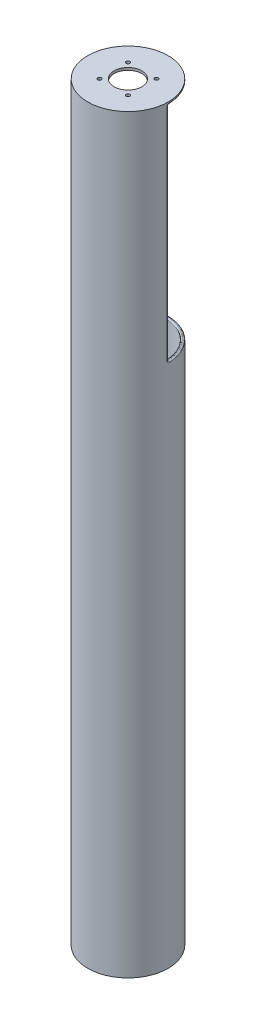
SolidWorks part; units mm, degrees
ref_plane "前视基准面" through (0, 0, 0) normal (0, 0, 1) x (1, 0, 0)
ref_plane "上视基准面" through (0, 0, 0) normal (0, 1, 0) x (1, 0, 0)
ref_plane "右视基准面" through (0, 0, 0) normal (1, 0, 0) x (0, 0, -1)
other "Configuration Table"
sketch "草图1" plane through (0, 0, 0) normal (0, 1, 0) x (1, 0, 0)
  circle A0 centre (0, 0) radius 32.5
  circle A1 centre (0, 0) radius 30
  dimension "D1" = 65
  dimension "D2" = 60
extrude "凸台-拉伸1" add sketch "草图1" along normal blind 340
sketch "草图2" plane through (0, 340, 0) normal (0, 1, 0) x (1, 0, 0)
  circle A0 centre (0, 0) radius 32.5
extrude "凸台-拉伸2" add sketch "草图2" along normal blind 5
sketch "草图8" plane through (0, 345, 0) normal (0, 1, 0) x (1, 0, 0)
  line L0 (-10.1, 10.1) -> (-10.1, -10.1) construction
  line L1 (10.1, -10.1) -> (10.1, 10.1) construction
  line L2 (-10.1, 10.1) -> (-10.1, -10.1) construction
  line L3 (10.1, -10.1) -> (10.1, 10.1) construction
  line L4 (10.3, -10.1) -> (10.3, 10.1)
  line L5 (8.1, 12.3) -> (-8.1, 12.3)
  line L6 (-10.3, 10.1) -> (-10.3, -10.1)
  line L7 (-8.1, -12.3) -> (8.1, -12.3)
  line L8 (-13.1, -3.3) -> (-13.1, 3.3) construction
  line L9 (-16.1, 2.4158) -> (-16.1, -2.4158) construction
  line L10 (-16.1, 0) -> (16.1, 0) construction
  line L11 (16.1, -2.4158) -> (16.1, 2.4158) construction
  line L12 (13.1, -3.3) -> (13.1, 3.3) construction
  line L20 (-8.7423, 11.1025) -> (-8.3294, 10.8824)
  line L21 (-9.2706, 9.1176) -> (-9.3647, 9.1678)
  line L22 (-10.1, 8.7267) -> (-10.1, 7.4004)
  line L23 (-11.416, 5.521) -> (-14.784, 4.2951)
  line L24 (-16.1, 2.4158) -> (-16.1, -2.4158)
  line L25 (-14.784, -4.2951) -> (-11.416, -5.521)
  line L26 (-10.1, -7.4004) -> (-10.1, -8.7267)
  line L27 (-9.3647, -9.1678) -> (-9.2706, -9.1176)
  line L28 (-8.3294, -10.8824) -> (-8.7423, -11.1025)
  line L29 (-8.1, -12.1) -> (8.1, -12.1)
  line L30 (8.7423, -11.1025) -> (8.3294, -10.8824)
  line L31 (9.2706, -9.1176) -> (9.3647, -9.1678)
  line L32 (10.1, -8.7267) -> (10.1, -7.4004)
  line L33 (11.416, -5.521) -> (14.784, -4.2951)
  line L34 (16.1, -2.4158) -> (16.1, 2.4158)
  line L35 (14.784, 4.2951) -> (11.416, 5.521)
  line L36 (10.1, 7.4004) -> (10.1, 8.7267)
  line L37 (9.3647, 9.1678) -> (9.2706, 9.1176)
  line L38 (8.3294, 10.8824) -> (8.7423, 11.1025)
  line L39 (8.1, 12.1) -> (-8.1, 12.1)
  line L42 (-10.1, 8.7267) -> (-10.1, 7.4004) construction
  line L46 (-10.1, -7.4004) -> (-10.1, -8.7267) construction
  line L49 (-8.1, -12.1) -> (8.1, -12.1) construction
  line L52 (10.1, -8.7267) -> (10.1, -7.4004) construction
  line L56 (10.1, 7.4004) -> (10.1, 8.7267) construction
  line L59 (8.1, 12.1) -> (-8.1, 12.1) construction
  arc A0 (-8.6427, 12.025) -> (-10.1, 10.1) centre (-8.1, 10.1) ccw construction
  arc A1 (10.1, 10.1) -> (8.6427, 12.025) centre (8.1, 10.1) ccw construction
  arc A2 (-10.1, -10.1) -> (-8.6427, -12.025) centre (-8.1, -10.1) ccw construction
  arc A3 (8.6427, -12.025) -> (10.1, -10.1) centre (8.1, -10.1) ccw construction
  arc A4 (-8.6427, 12.025) -> (-10.1, 10.1) centre (-8.1, 10.1) ccw construction
  arc A5 (10.1, 10.1) -> (8.6427, 12.025) centre (8.1, 10.1) ccw construction
  arc A6 (-10.1, -10.1) -> (-8.6427, -12.025) centre (-8.1, -10.1) ccw construction
  arc A7 (8.6427, -12.025) -> (10.1, -10.1) centre (8.1, -10.1) ccw construction
  arc A8 (10.3, 10.1) -> (8.6969, 12.2175) centre (8.1, 10.1) ccw
  arc A9 (8.6969, 12.2175) -> (8.1, 12.3) centre (8.1, 10.1) ccw
  arc A10 (-8.1, 12.3) -> (-8.6969, 12.2175) centre (-8.1, 10.1) ccw
  arc A11 (-8.6969, 12.2175) -> (-10.3, 10.1) centre (-8.1, 10.1) ccw
  arc A12 (-10.3, -10.1) -> (-8.6969, -12.2175) centre (-8.1, -10.1) ccw
  arc A13 (-8.6969, -12.2175) -> (-8.1, -12.3) centre (-8.1, -10.1) ccw
  arc A14 (8.1, -12.3) -> (8.6969, -12.2175) centre (8.1, -10.1) ccw
  arc A15 (8.6969, -12.2175) -> (10.3, -10.1) centre (8.1, -10.1) ccw
  arc A16 (-11.6, 1.8) -> (-14.6, 1.8) centre (-13.1, 1.8) ccw construction
  arc A17 (14.6, 1.8) -> (11.6, 1.8) centre (13.1, 1.8) ccw construction
  circle A18 centre (-13.1, 0) radius 1.5
  circle A19 centre (13.1, 0) radius 1.5
  arc A28 (-8.1, 12.1) -> (-8.6427, 12.025) centre (-8.1, 10.1) ccw
  arc A29 (-8.6427, 12.025) -> (-8.7423, 11.1025) centre (-8.507, 11.5437) ccw
  arc A30 (-9.2706, 9.1176) -> (-8.3294, 10.8824) centre (-8.8, 10) ccw
  arc A31 (-9.3647, 9.1678) -> (-9.6, 9.2267) centre (-9.6, 8.7267) ccw
  arc A32 (-9.6, 9.2267) -> (-10.1, 8.7267) centre (-9.6, 8.7267) ccw
  arc A33 (-11.416, 5.521) -> (-10.1, 7.4004) centre (-12.1, 7.4004) ccw
  arc A34 (-14.784, 4.2951) -> (-16.1, 2.4158) centre (-14.1, 2.4158) ccw
  arc A35 (-16.1, -2.4158) -> (-14.784, -4.2951) centre (-14.1, -2.4158) ccw
  arc A36 (-10.1, -7.4004) -> (-11.416, -5.521) centre (-12.1, -7.4004) ccw
  arc A37 (-10.1, -8.7267) -> (-9.3647, -9.1678) centre (-9.6, -8.7267) ccw
  arc A38 (-8.8, -9) -> (-9.2706, -9.1176) centre (-8.8, -10) ccw
  arc A39 (-8.3294, -10.8824) -> (-8.8, -9) centre (-8.8, -10) ccw
  arc A40 (-8.7423, -11.1025) -> (-8.6427, -12.025) centre (-8.507, -11.5437) ccw
  arc A41 (-8.6427, -12.025) -> (-8.1, -12.1) centre (-8.1, -10.1) ccw
  arc A42 (8.1, -12.1) -> (8.6427, -12.025) centre (8.1, -10.1) ccw
  arc A43 (8.6427, -12.025) -> (8.7423, -11.1025) centre (8.507, -11.5437) ccw
  arc A44 (8.8, -9) -> (8.3294, -10.8824) centre (8.8, -10) ccw
  arc A45 (9.2706, -9.1176) -> (8.8, -9) centre (8.8, -10) ccw
  arc A46 (9.3647, -9.1678) -> (10.1, -8.7267) centre (9.6, -8.7267) ccw
  arc A47 (11.416, -5.521) -> (10.1, -7.4004) centre (12.1, -7.4004) ccw
  arc A48 (14.784, -4.2951) -> (16.1, -2.4158) centre (14.1, -2.4158) ccw
  arc A49 (16.1, 2.4158) -> (14.784, 4.2951) centre (14.1, 2.4158) ccw
  arc A50 (10.1, 7.4004) -> (11.416, 5.521) centre (12.1, 7.4004) ccw
  arc A51 (10.1, 8.7267) -> (9.6, 9.2267) centre (9.6, 8.7267) ccw
  arc A52 (9.6, 9.2267) -> (9.3647, 9.1678) centre (9.6, 8.7267) ccw
  arc A53 (8.3294, 10.8824) -> (9.2706, 9.1176) centre (8.8, 10) ccw
  arc A54 (8.7423, 11.1025) -> (8.6427, 12.025) centre (8.507, 11.5437) ccw
  arc A55 (8.6427, 12.025) -> (8.1, 12.1) centre (8.1, 10.1) ccw
  arc A56 (-8.1, 12.1) -> (-8.6427, 12.025) centre (-8.1, 10.1) ccw construction
  arc A69 (-8.6427, -12.025) -> (-8.1, -12.1) centre (-8.1, -10.1) ccw construction
  arc A70 (8.1, -12.1) -> (8.6427, -12.025) centre (8.1, -10.1) ccw construction
  arc A83 (8.6427, 12.025) -> (8.1, 12.1) centre (8.1, 10.1) ccw construction
  dimension "D1" = 0
  dimension "D2" = 0.2
extrude "切除-拉伸2" cut sketch "草图8" against normal blind 5
sketch "草图9" plane through (0, 345, 0) normal (0, 1, 0) x (1, 0, 0)
  circle A2 centre (0, 0) radius 32.5
  circle A3 centre (0, 0) radius 30
  dimension "D1" = 60
  dimension "D2" = 65
extrude "凸台-拉伸3" add sketch "草图9" along normal blind 260
sketch "草图10" plane through (0, 605, 0) normal (0, 1, 0) x (1, 0, 0)
  circle A0 centre (0, 0) radius 32.5
extrude "凸台-拉伸4" add sketch "草图10" along normal blind 2
sketch "草图12" plane through (0, 607, 0) normal (0, 1, 0) x (1, 0, 0)
  arc A0 (-12.75, 11.5) -> (-10.25, 11.5) centre (-11.5, 11.5) ccw construction
  arc A1 (10.25, 11.5) -> (12.75, 11.5) centre (11.5, 11.5) ccw construction
  arc A2 (12.75, 11.5) -> (10.25, 11.5) centre (11.5, 11.5) ccw construction
  arc A3 (-10.25, 11.5) -> (-12.75, 11.5) centre (-11.5, 11.5) ccw construction
  arc A4 (-12.75, -11.5) -> (-10.25, -11.5) centre (-11.5, -11.5) ccw construction
  arc A5 (-10.25, -11.5) -> (-12.75, -11.5) centre (-11.5, -11.5) ccw construction
  arc A6 (10.25, -11.5) -> (12.75, -11.5) centre (11.5, -11.5) ccw construction
  arc A7 (12.75, -11.5) -> (10.25, -11.5) centre (11.5, -11.5) ccw construction
  arc A8 (12.95, 11.5) -> (10.05, 11.5) centre (11.5, 11.5) ccw
  arc A9 (10.05, 11.5) -> (12.95, 11.5) centre (11.5, 11.5) ccw
  arc A10 (12.95, -11.5) -> (10.05, -11.5) centre (11.5, -11.5) ccw
  arc A11 (-12.75, 11.5) -> (-10.25, 11.5) centre (-11.5, 11.5) ccw construction
  arc A12 (10.25, 11.5) -> (12.75, 11.5) centre (11.5, 11.5) ccw construction
  arc A13 (12.75, 11.5) -> (10.25, 11.5) centre (11.5, 11.5) ccw construction
  arc A14 (-10.25, 11.5) -> (-12.75, 11.5) centre (-11.5, 11.5) ccw construction
  arc A15 (-12.75, -11.5) -> (-10.25, -11.5) centre (-11.5, -11.5) ccw construction
  arc A16 (-10.25, -11.5) -> (-12.75, -11.5) centre (-11.5, -11.5) ccw construction
  arc A17 (10.25, -11.5) -> (12.75, -11.5) centre (11.5, -11.5) ccw construction
  arc A18 (12.75, -11.5) -> (10.25, -11.5) centre (11.5, -11.5) ccw construction
  arc A22 (11.2, 0) -> (-11.2, 0) centre (0, 0) ccw
  arc A23 (-11.2, 0) -> (11.2, 0) centre (0, 0) ccw
  arc A24 (11, 0) -> (-11, 0) centre (0, 0) ccw
  arc A25 (-11, 0) -> (11, 0) centre (0, 0) ccw
  arc A26 (11, 0) -> (-11, 0) centre (0, 0) ccw construction
  arc A27 (-11, 0) -> (11, 0) centre (0, 0) ccw construction
  arc A28 (10.05, -11.5) -> (12.95, -11.5) centre (11.5, -11.5) ccw
  arc A29 (-10.05, -11.5) -> (-12.95, -11.5) centre (-11.5, -11.5) ccw
  arc A30 (-12.95, -11.5) -> (-10.05, -11.5) centre (-11.5, -11.5) ccw
  arc A31 (-10.05, 11.5) -> (-12.95, 11.5) centre (-11.5, 11.5) ccw
  arc A32 (-12.95, 11.5) -> (-10.05, 11.5) centre (-11.5, 11.5) ccw
  dimension "D1" = 0
  dimension "D2" = 0.2
  dimension "D3" = 0.2
extrude "切除-拉伸3" cut sketch "草图12" against normal blind 2
sketch "草图14" plane through (0, 0, 0) normal (0, 0, 1) x (1, 0, 0)
  line L1 (-32.5, 605) -> (32.5, 605)
  line L2 (-32.5, 605) -> (-32.5, 425)
  line L3 (-32.5, 425) -> (32.5, 425)
  line L4 (32.5, 605) -> (32.5, 425)
  line L5 (-32.5, 607) -> (-32.5, 0) construction
  line L6 (32.5, 0) -> (32.5, 607) construction
  line L7 (-30, 605) -> (30, 605) construction
  dimension "D1" = 180
extrude "切除-拉伸4" cut sketch "草图14" against normal blind 32.5
fillet "圆角1" radius 1 12 edges at (0, 605, 30) (0, 425, -30) (0, 605, -32.5) (0, 425, -32.5) (32.5, 515, 0) (-32.5, 515, 0) (-31.25, 605, 0) (31.25, 605, 0) (-30, 515, 0) (30, 515, 0) (-31.25, 425, 0) (31.25, 425, 0)
